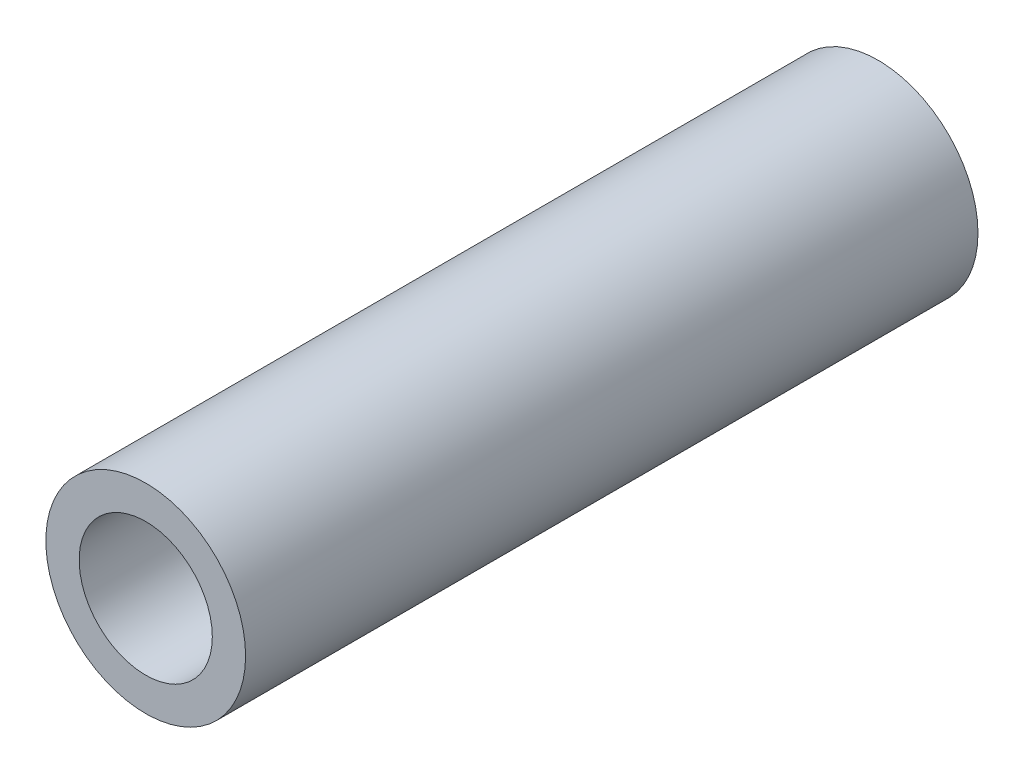
SolidWorks part; units mm, degrees
ref_plane "Front Plane" through (0, 0, 0) normal (0, 0, 1) x (1, 0, 0)
ref_plane "Top Plane" through (0, 0, 0) normal (0, 1, 0) x (1, 0, 0)
ref_plane "Right Plane" through (0, 0, 0) normal (1, 0, 0) x (0, 0, -1)
sketch "Sketch1" plane through (0, 0, 0) normal (0, 0, 1) x (1, 0, 0)
  circle A0 centre (0, 0) radius 37.5
  circle A1 centre (0, 0) radius 25
  dimension "D1" = 75
  dimension "D2" = 50
extrude "Boss-Extrude1" add sketch "Sketch1" along normal blind 275
